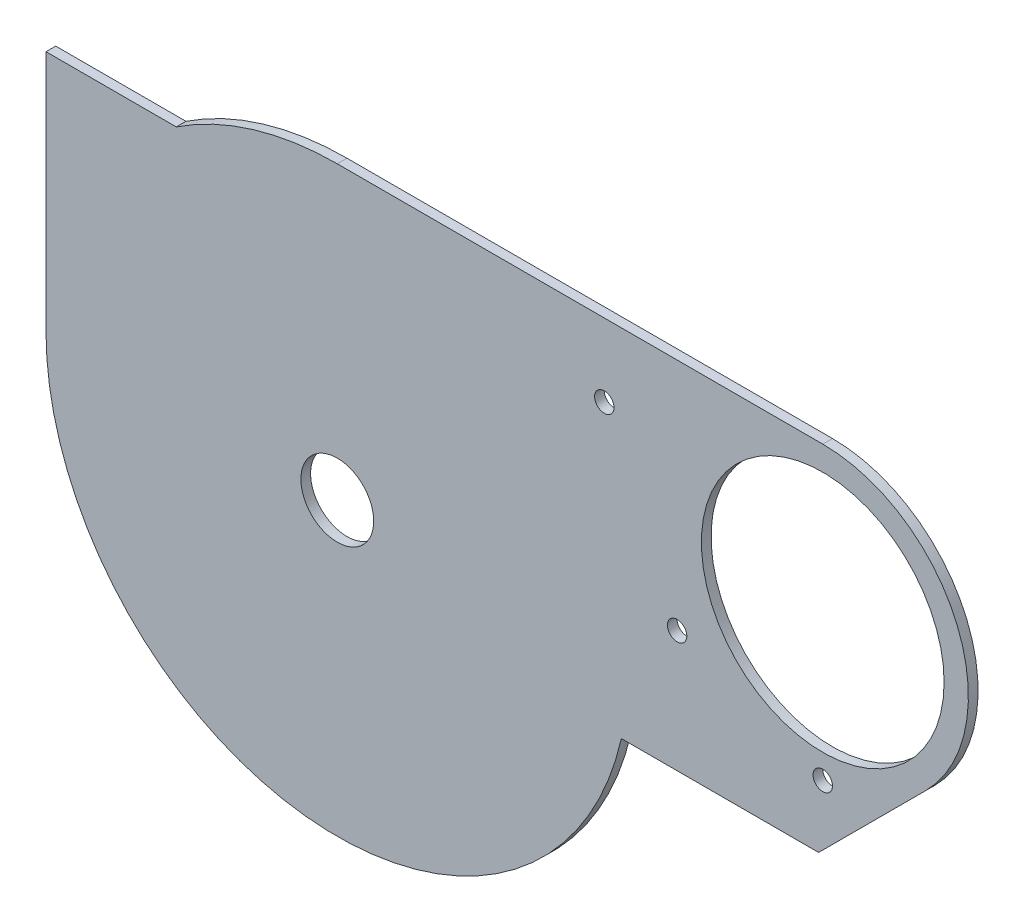
SolidWorks part; units mm, degrees
ref_plane "前视基准面" through (0, 0, 0) normal (0, 0, 1) x (1, 0, 0)
ref_plane "上视基准面" through (0, 0, 0) normal (0, 1, 0) x (1, 0, 0)
ref_plane "右视基准面" through (0, 0, 0) normal (1, 0, 0) x (0, 0, -1)
sketch "Sketch1" plane through (0, 0, 0) normal (0, 0, 1) x (1, 0, 0)
  line L0 (-26.5591, 60) -> (97.717, 60) construction
  line L3 (-33.1662, 50) -> (-60, 50)
  line L4 (-60, 0) -> (-60, 50)
  line L5 (100, 60) -> (0, 60)
  line L6 (73.5456, -38.8808) -> (87.301, -25.1254) construction
  line L7 (106.8791, 60) -> (171.5951, 60) construction
  line L10 (99.1522, -13.2742) -> (121.2132, 8.7868)
  line L11 (58.5132, -13.2742) -> (99.1522, -13.2742)
  arc A0 (0, 60) -> (58.5132, -13.2742) centre (0, 0) ccw
  circle A2 centre (0, 0) radius 7.5
  arc A4 (121.2132, 8.7868) -> (100, 60) centre (100, 30) ccw
  circle A7 centre (100, 30) radius 25
  dimension "D1" = 120
  dimension "D2" = 100
  dimension "D5" = 60
extrude "Boss-Extrude1" add sketch "Sketch1" along normal blind 2
sketch "Sketch2" plane through (0, 0, 2) normal (0, 0, 1) x (1, 0, 0)
  line L0 (100, 60) -> (0, 60) construction
  line L1 (-60, 0) -> (-60, 50) construction
  line L5 (125, 30) -> (100, 5) construction
  line L6 (115.7514, 14.2486) -> (82.3223, 47.6777) construction
  line L7 (58.5132, -13.2742) -> (99.1522, -13.2742) construction
  circle A1 centre (0, 0) radius 57
  circle A2 centre (55, 45) radius 2
  circle A3 centre (70, 11.7258) radius 2
  circle A4 centre (96.4645, 33.5355) radius 15
  circle A5 centre (100, 30) radius 25 construction
  dimension "D1" = 15
  dimension "D4" = 130
  dimension "D5" = 20
  dimension "D2" = 115
  dimension "D3" = 25
extrude "Cut-Extrude1" cut sketch "Sketch2" against normal up to next contours A2 | A3
sketch "Sketch3" plane through (0, 0, 2) normal (0, 0, 1) x (1, 0, 0)
  circle A0 centre (100, 0) radius 2
  circle A1 centre (100, 30) radius 25 construction
  dimension "D1" = 30
extrude "Cut-Extrude2" cut sketch "Sketch3" against normal blind 10
